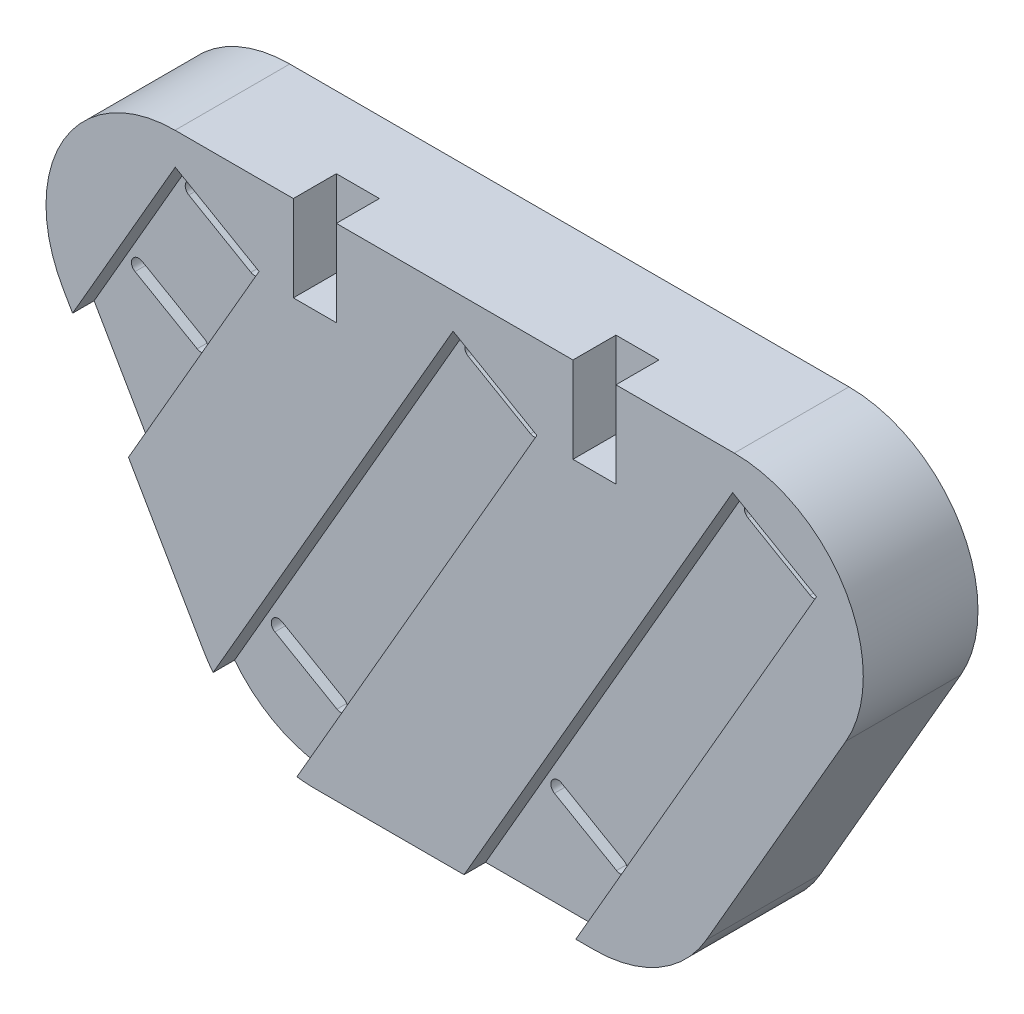
SolidWorks part; units mm, degrees
ref_plane "Front Plane" through (0, 0, 0) normal (0, 0, 1) x (1, 0, 0)
ref_plane "Top Plane" through (0, 0, 0) normal (0, 1, 0) x (1, 0, 0)
ref_plane "Right Plane" through (0, 0, 0) normal (1, 0, 0) x (0, 0, -1)
sketch "Sketch1" plane through (0, 0, 0) normal (0, 0, 1) x (1, 0, 0)
  line L0 (0, 0) -> (-19.5, 0) construction
  line L1 (-9.75, -16.8875) -> (-29.25, -16.8875) construction
  line L2 (0, 0) -> (-9.75, -16.8875) construction
  line L3 (-9.75, -16.8875) -> (-19.5, 0) construction
  line L4 (-19.5, 0) -> (-29.25, -16.8875) construction
  line L5 (-29.25, -16.8875) -> (-39, 0) construction
  line L6 (-39, 0) -> (-19.5, 0) construction
  line L7 (8.9827, 0.5584) -> (-5.4199, -24.3875) construction
  line L8 (-5.4199, -24.3875) -> (-33.5801, -24.3875) construction
  line L9 (-33.5801, -24.3875) -> (-47.9827, 0.5584) construction
  line L10 (-43.9749, 7.5) -> (4.9749, 7.5) construction
  line L11 (7.7942, -4.5) -> (-1.9558, -21.3875)
  line L12 (-9.75, -25.8875) -> (-29.25, -25.8875)
  line L13 (-37.0442, -21.3875) -> (-46.7942, -4.5)
  line L14 (-39, 9) -> (0, 9)
  line L15 (1.7814, -11.9145) -> (3.0804, -12.6645) construction
  line L16 (-19.5, -24.3875) -> (-19.5, -25.8875) construction
  line L17 (-40.7814, -11.9145) -> (-42.0804, -12.6645) construction
  line L18 (-19.5, 7.5) -> (-19.5, 9) construction
  circle A0 centre (-29.25, -16.8875) radius 7.5
  circle A1 centre (-19.5, 0) radius 7.5
  circle A2 centre (0, 0) radius 7.5
  circle A3 centre (0, 0) radius 7.5
  circle A4 centre (-9.75, -16.8875) radius 7.5
  circle A5 centre (-39, 0) radius 7.5
  arc A6 (7.7942, -4.5) -> (0, 9) centre (0, 0) ccw
  arc A7 (-39, 9) -> (-46.7942, -4.5) centre (-39, 0) ccw
  arc A8 (-1.9558, -21.3875) -> (-9.75, -25.8875) centre (-9.75, -16.8875) cw
  arc A9 (-29.25, -25.8875) -> (-37.0442, -21.3875) centre (-29.25, -16.8875) cw
  point P28 (1.7814, -11.9145)
  point P30 (-19.5, -24.3875)
  point P32 (-40.7814, -11.9145)
  point P35 (-19.5, 9)
  dimension "D2" = 15
  dimension "D3" = 19.5
  dimension "D4" = 1.5
  dimension "D5" = 1.5
  dimension "D1" = 0.25
extrude "Boss-Extrude1" add sketch "Sketch1" along normal blind 5
sketch "Sketch2" plane through (0, 0, 5) normal (0, 0, 1) x (1, 0, 0)
  line L0 (-1.9558, -21.3875) -> (7.7942, -4.5) construction
  line L1 (0, 9) -> (-39, 9) construction
  line L2 (-46.7942, -4.5) -> (-37.0442, -21.3875) construction
  line L3 (-29.25, -25.8875) -> (-9.75, -25.8875) construction
  line L4 (-1.9558, -21.3875) -> (7.7942, -4.5)
  line L5 (0, 9) -> (-39, 9)
  line L6 (-46.7942, -4.5) -> (-37.0442, -21.3875)
  line L7 (-29.25, -25.8875) -> (-9.75, -25.8875)
  line L8 (4.0401, 1.9976) -> (-0.2901, 4.4976) construction
  line L9 (3.7901, 1.5646) -> (-0.5401, 4.0646)
  line L10 (4.2901, 2.4306) -> (-0.0401, 4.9306)
  line L11 (-9.4599, -21.3851) -> (-13.7901, -18.8851) construction
  line L12 (-9.7099, -21.8181) -> (-14.0401, -19.3181)
  line L13 (-9.2099, -20.9521) -> (-13.5401, -18.4521)
  line L14 (1.875, 3.2476) -> (-11.625, -20.1351) construction
  line L15 (-31.125, -20.1351) -> (-29.25, -16.8875) construction
  line L16 (0, 0) -> (1.875, 3.2476) construction
  line L17 (1.875, 3.2476) -> (3.75, 6.4952) construction
  line L18 (-11.625, -20.1351) -> (-13.5, -23.3827) construction
  line L19 (-11.625, -20.1351) -> (-9.75, -16.8875) construction
  line L20 (-17.625, 3.2476) -> (-15.75, 6.4952) construction
  line L21 (-17.625, 3.2476) -> (-31.125, -20.1351) construction
  line L22 (-19.5, 0) -> (-17.625, 3.2476) construction
  line L23 (-31.125, -20.1351) -> (-33, -23.3827) construction
  line L24 (-15.4599, 1.9976) -> (-19.7901, 4.4976) construction
  line L25 (-15.7099, 1.5646) -> (-20.0401, 4.0646)
  line L26 (-15.2099, 2.4306) -> (-19.5401, 4.9306)
  line L27 (-28.9599, -21.3851) -> (-33.2901, -18.8851) construction
  line L28 (-29.2099, -21.8181) -> (-33.5401, -19.3181)
  line L29 (-28.7099, -20.9521) -> (-33.0401, -18.4521)
  line L30 (-34.9599, 1.9976) -> (-39.2901, 4.4976) construction
  line L31 (-35.2099, 1.5646) -> (-39.5401, 4.0646)
  line L32 (-34.7099, 2.4306) -> (-39.0401, 4.9306)
  line L33 (-38.7099, -4.4976) -> (-43.0401, -1.9976) construction
  line L34 (-38.9599, -4.9306) -> (-43.2901, -2.4306)
  line L35 (-38.4599, -4.0646) -> (-42.7901, -1.5646)
  line L36 (-37.125, 3.2476) -> (-40.875, -3.2476) construction
  line L37 (-37.125, 3.2476) -> (-35.25, 6.4952) construction
  line L38 (-40.875, -3.2476) -> (-42.75, -6.4952) construction
  line L39 (-37.125, 3.2476) -> (-39, 0) construction
  arc A0 (-9.75, -25.8875) -> (-1.9558, -21.3875) centre (-9.75, -16.8875) ccw construction
  arc A1 (7.7942, -4.5) -> (0, 9) centre (0, 0) ccw construction
  arc A2 (-39, 9) -> (-46.7942, -4.5) centre (-39, 0) ccw construction
  arc A3 (-37.0442, -21.3875) -> (-29.25, -25.8875) centre (-29.25, -16.8875) ccw construction
  arc A4 (-9.75, -25.8875) -> (-1.9558, -21.3875) centre (-9.75, -16.8875) ccw
  arc A5 (7.7942, -4.5) -> (0, 9) centre (0, 0) ccw
  arc A6 (-39, 9) -> (-46.7942, -4.5) centre (-39, 0) ccw
  arc A7 (-37.0442, -21.3875) -> (-29.25, -25.8875) centre (-29.25, -16.8875) ccw
  circle A8 centre (-39, 0) radius 7.5 construction
  circle A9 centre (-29.25, -16.8875) radius 7.5 construction
  circle A10 centre (-19.5, 0) radius 7.5 construction
  circle A11 centre (-9.75, -16.8875) radius 7.5 construction
  circle A12 centre (0, 0) radius 7.5 construction
  circle A13 centre (-39, 0) radius 7.5
  circle A14 centre (-29.25, -16.8875) radius 7.5
  circle A15 centre (-19.5, 0) radius 7.5
  circle A16 centre (-9.75, -16.8875) radius 7.5
  circle A17 centre (0, 0) radius 7.5
  arc A18 (3.7901, 1.5646) -> (4.2901, 2.4306) centre (4.0401, 1.9976) ccw
  arc A19 (-0.0401, 4.9306) -> (-0.5401, 4.0646) centre (-0.2901, 4.4976) ccw
  arc A20 (-9.7099, -21.8181) -> (-9.2099, -20.9521) centre (-9.4599, -21.3851) ccw
  arc A21 (-13.5401, -18.4521) -> (-14.0401, -19.3181) centre (-13.7901, -18.8851) ccw
  arc A22 (-15.7099, 1.5646) -> (-15.2099, 2.4306) centre (-15.4599, 1.9976) ccw
  arc A23 (-19.5401, 4.9306) -> (-20.0401, 4.0646) centre (-19.7901, 4.4976) ccw
  arc A24 (-29.2099, -21.8181) -> (-28.7099, -20.9521) centre (-28.9599, -21.3851) ccw
  arc A25 (-33.0401, -18.4521) -> (-33.5401, -19.3181) centre (-33.2901, -18.8851) ccw
  arc A26 (-35.2099, 1.5646) -> (-34.7099, 2.4306) centre (-34.9599, 1.9976) ccw
  arc A27 (-39.0401, 4.9306) -> (-39.5401, 4.0646) centre (-39.2901, 4.4976) ccw
  arc A28 (-38.9599, -4.9306) -> (-38.4599, -4.0646) centre (-38.7099, -4.4976) ccw
  arc A29 (-42.7901, -1.5646) -> (-43.2901, -2.4306) centre (-43.0401, -1.9976) ccw
  point P8 (-37.125, 3.2476)
  point P25 (1.875, 3.2476)
  point P32 (-11.625, -20.1351)
  point P45 (-17.625, 3.2476)
  point P52 (-31.125, -20.1351)
  point P64 (-40.875, -3.2476)
  circle M1 centre (-9.75, -16.8875) radius 7.5
  circle M2 centre (0, 0) radius 7.5
  arc M3 (7.7942, -4.5) -> (0, 9) centre (0, 0) ccw
  line M4 (0, 9) -> (-39, 9)
  arc M5 (-39, 9) -> (-46.7942, -4.5) centre (-39, 0) ccw
  line M6 (-46.7942, -4.5) -> (-37.0442, -21.3875)
  arc M7 (-37.0442, -21.3875) -> (-29.25, -25.8875) centre (-29.25, -16.8875) ccw
  line M8 (-29.25, -25.8875) -> (-9.75, -25.8875)
  arc M9 (-9.75, -25.8875) -> (-1.9558, -21.3875) centre (-9.75, -16.8875) ccw
  line M10 (-1.9558, -21.3875) -> (7.7942, -4.5)
  circle M11 centre (-19.5, 0) radius 7.5
  circle M12 centre (-29.25, -16.8875) radius 7.5
  circle M13 centre (-39, 0) radius 7.5
  dimension "D1" = 1
  dimension "D2" = 5
extrude "Boss-Extrude2" add sketch "Sketch2" along normal blind 1.5 contours A21 L13 A20 L12 M1 | M10 M3 M4 M5 M6 M7 M8 M9 M2 M11 M13 M12 M1 | A19 L10 A18 L9 M2 | A23 L26 A22 L25 M11 | A25 L29 A24 L28 M12 | A29 L35 A28 L34 A27 L32 A26 L31 M13
sketch "Sketch3" plane through (0, 0, 6.5) normal (0, 0, 1) x (1, 0, 0)
  line L0 (-46.7942, -4.5) -> (-37.0442, -21.3875) construction
  line L1 (-29.25, -25.8875) -> (-9.75, -25.8875) construction
  line L2 (-1.9558, -21.3875) -> (7.7942, -4.5) construction
  line L3 (0, 9) -> (-39, 9) construction
  line L4 (-46.7942, -4.5) -> (-37.0442, -21.3875)
  line L5 (-29.25, -25.8875) -> (-9.75, -25.8875)
  line L6 (-1.9558, -21.3875) -> (7.7942, -4.5)
  line L7 (0, 9) -> (-39, 9)
  line L8 (5.7353, 3.1839) -> (-9.6397, -23.4464)
  line L9 (5.7353, 3.1839) -> (-0.1103, 6.5589)
  line L10 (-9.6397, -23.4464) -> (-15.4853, -20.0714)
  line L11 (-0.1103, 6.5589) -> (-15.4853, -20.0714)
  line L12 (5.7353, 3.1839) -> (-15.4853, -20.0714) construction
  line L13 (-9.6397, -23.4464) -> (-0.1103, 6.5589) construction
  line L14 (-11.625, -20.1351) -> (-13.5, -23.3827) construction
  line L15 (-11.625, -20.1351) -> (-13.5, -23.3827) construction
  line L16 (-11.875, -20.5681) -> (-12.5625, -21.7589) construction
  line L17 (-9.7099, -21.8181) -> (-14.0401, -19.3181) construction
  line L18 (-14.2231, -18.6351) -> (-14.5478, -18.4476) construction
  line L19 (1.875, 3.2476) -> (-11.625, -20.1351) construction
  line L20 (1.875, 3.2476) -> (-11.625, -20.1351) construction
  line L21 (-31.125, -20.1351) -> (-33, -23.3827) construction
  line L22 (-17.625, 3.2476) -> (-31.125, -20.1351) construction
  line L23 (-31.125, -20.1351) -> (-33, -23.3827) construction
  line L24 (-17.625, 3.2476) -> (-31.125, -20.1351) construction
  line L25 (-13.7647, 3.1839) -> (-29.1397, -23.4464)
  line L26 (-13.7647, 3.1839) -> (-19.6103, 6.5589)
  line L27 (-29.1397, -23.4464) -> (-34.9853, -20.0714)
  line L28 (-19.6103, 6.5589) -> (-34.9853, -20.0714)
  line L29 (-13.7647, 3.1839) -> (-34.9853, -20.0714) construction
  line L30 (-29.1397, -23.4464) -> (-19.6103, 6.5589) construction
  line L31 (-32.8571, -19.1351) -> (-34.0478, -18.4476) construction
  line L32 (-31.375, -20.5681) -> (-32.0625, -21.7589) construction
  line L33 (-29.2099, -21.8181) -> (-33.5401, -19.3181) construction
  line L34 (-33.1397, 3.4004) -> (-42.2476, -12.375)
  line L35 (-33.1397, 3.4004) -> (-38.9853, 6.7754)
  line L36 (-9.6397, -23.4464) -> (-15.4853, -20.0714)
  line L37 (-38.9853, 6.7754) -> (-46.1447, -5.625)
  line L38 (-33.1397, 3.4004) -> (-45.4579, -6.8146) construction
  line L39 (-42.2476, -12.375) -> (-38.9853, 6.7754) construction
  line L40 (-37.125, 3.2476) -> (-40.875, -3.2476) construction
  line L41 (-36.875, 3.6806) -> (-36.0625, 5.0879) construction
  line L42 (-34.7099, 2.4306) -> (-39.0401, 4.9306) construction
  line L43 (-36.0625, 5.0879) -> (-35.25, 6.4952) construction
  line L44 (-9.6397, -23.4464) -> (-11.049, -25.8875)
  line L45 (-15.4853, -20.0714) -> (-18.8433, -25.8875)
  line L47 (-29.1397, -23.4464) -> (-34.9853, -20.0714)
  line L48 (-29.1397, -23.4464) -> (-30.4988, -25.8004)
  line L49 (-34.9853, -20.0714) -> (-36.3444, -22.4254)
  arc A0 (-37.0442, -21.3875) -> (-29.25, -25.8875) centre (-29.25, -16.8875) ccw construction
  arc A1 (-9.75, -25.8875) -> (-1.9558, -21.3875) centre (-9.75, -16.8875) ccw construction
  arc A2 (7.7942, -4.5) -> (0, 9) centre (0, 0) ccw construction
  arc A3 (-39, 9) -> (-46.7942, -4.5) centre (-39, 0) ccw construction
  arc A4 (-37.0442, -21.3875) -> (-29.25, -25.8875) centre (-29.25, -16.8875) ccw
  arc A5 (-9.75, -25.8875) -> (-1.9558, -21.3875) centre (-9.75, -16.8875) ccw
  arc A6 (7.7942, -4.5) -> (0, 9) centre (0, 0) ccw
  arc A7 (-39, 9) -> (-46.7942, -4.5) centre (-39, 0) ccw
  arc A8 (-13.5401, -18.4521) -> (-14.0401, -19.3181) centre (-13.7901, -18.8851) ccw construction
  arc A9 (-33.0401, -18.4521) -> (-33.5401, -19.3181) centre (-33.2901, -18.8851) ccw construction
  point P13 (-4.875, -8.4437)
  point P30 (-12.5625, -21.7589)
  point P33 (-4.875, -8.4437)
  point P35 (-24.375, -8.4437)
  point P49 (-24.375, -8.4437)
  point P50 (-40.6165, -2.7998)
  line M15 (-1.9558, -21.3875) -> (7.7942, -4.5)
  arc M16 (7.7942, -4.5) -> (0, 9) centre (0, 0) ccw
  line M17 (0, 9) -> (-39, 9)
  arc M18 (-39, 9) -> (-46.7942, -4.5) centre (-39, 0) ccw
  line M19 (-46.7942, -4.5) -> (-37.0442, -21.3875)
  arc M20 (-37.0442, -21.3875) -> (-29.25, -25.8875) centre (-29.25, -16.8875) ccw
  line M21 (-29.25, -25.8875) -> (-9.75, -25.8875)
  arc M22 (-9.75, -25.8875) -> (-1.9558, -21.3875) centre (-9.75, -16.8875) ccw
extrude "Boss-Extrude3" add sketch "Sketch3" along normal blind 1.5 contours L37 L35 L34 L4 L28 L26 L25 L27 L11 L9 L8 L10 M20 M21 M22 M15 M16 M17 M18 M19
sketch "Sketch9" plane through (0, 0, 8) normal (0, 0, 1) x (1, 0, 0)
  line L0 (-39, 9) -> (-19.5, 9)
  line L1 (0, 9) -> (-39, 9) construction
  line L2 (-19.5, 9) -> (0, 9) construction
  line L3 (-29.25, 9) -> (-29.25, 3) construction
  line L4 (-27.75, 3) -> (-30.75, 3)
  line L5 (-27.75, 3) -> (-27.75, 9)
  line L6 (-27.75, 9) -> (-30.75, 9)
  line L7 (-30.75, 3) -> (-30.75, 9)
  line L8 (-27.75, 3) -> (-30.75, 9) construction
  line L9 (-27.75, 9) -> (-30.75, 3) construction
  line L10 (-8.25, 3) -> (-11.25, 3)
  line L11 (-8.25, 3) -> (-8.25, 9)
  line L12 (-8.25, 9) -> (-11.25, 9)
  line L13 (-11.25, 3) -> (-11.25, 9)
  line L14 (-8.25, 3) -> (-11.25, 9) construction
  line L15 (-8.25, 9) -> (-11.25, 3) construction
  line L16 (-9.75, 9) -> (-9.75, 3) construction
  point P5 (-29.25, 6)
  point P12 (-9.75, 6)
  dimension "D1" = 3
  dimension "D2" = 6
extrude "Cut-Extrude4" cut sketch "Sketch9" against normal blind 3 contours L10 L13 L12 L11 | L4 L7 L6 L5
sketch "Sketch4" plane through (0, 0, 0) normal (0, 0, -1) x (-1, 0, 0)
  line L0 (29.25, -25.8875) -> (9.75, -25.8875) construction
  line L1 (22, -25.8875) -> (17, -25.8875)
  line L2 (22, -25.8875) -> (22, -22.8875)
  line L3 (22, -22.8875) -> (17, -22.8875)
  line L4 (17, -25.8875) -> (17, -22.8875)
  line L5 (22, -25.8875) -> (17, -22.8875) construction
  line L6 (22, -22.8875) -> (17, -25.8875) construction
  line L7 (29.25, -25.8875) -> (9.75, -25.8875)
  line L8 (0, 9) -> (39, 9) construction
  line L9 (46.7942, -4.5) -> (37.0442, -21.3875) construction
  line L10 (1.9558, -21.3875) -> (-7.7942, -4.5) construction
  line L11 (0, 9) -> (39, 9)
  line L12 (46.7942, -4.5) -> (37.0442, -21.3875)
  line L13 (1.9558, -21.3875) -> (-7.7942, -4.5)
  line L14 (40.5712, -9.2787) -> (43.1692, -10.7787)
  line L15 (40.5712, -9.2787) -> (38.0712, -13.6088)
  line L16 (43.1692, -10.7787) -> (40.6692, -15.1088)
  line L17 (38.0712, -13.6088) -> (40.6692, -15.1088)
  line L18 (40.5712, -9.2787) -> (40.6692, -15.1088) construction
  line L19 (43.1692, -10.7787) -> (38.0712, -13.6088) construction
  line L20 (-1.5712, -9.2787) -> (-4.1692, -10.7787)
  line L21 (-1.5712, -9.2787) -> (0.9288, -13.6088)
  line L22 (-4.1692, -10.7787) -> (-1.6692, -15.1088)
  line L23 (0.9288, -13.6088) -> (-1.6692, -15.1088)
  line L24 (-1.5712, -9.2787) -> (-1.6692, -15.1088) construction
  line L25 (-4.1692, -10.7787) -> (0.9288, -13.6088) construction
  line L26 (41.9192, -12.9437) -> (3.9115, 9) construction
  line L27 (12.25, 6) -> (7.25, 6)
  line L28 (12.25, 6) -> (12.25, 9)
  line L29 (12.25, 9) -> (7.25, 9)
  line L30 (7.25, 6) -> (7.25, 9)
  line L31 (12.25, 6) -> (7.25, 9) construction
  line L32 (12.25, 9) -> (7.25, 6) construction
  line L33 (31.75, 6) -> (26.75, 6)
  line L34 (31.75, 6) -> (31.75, 9)
  line L35 (31.75, 9) -> (26.75, 9)
  line L36 (26.75, 6) -> (26.75, 9)
  line L37 (31.75, 6) -> (26.75, 9) construction
  line L38 (31.75, 9) -> (26.75, 6) construction
  line L39 (-2.9192, -12.9437) -> (35.0885, 9) construction
  line L40 (22, -24.3875) -> (17, -24.3875)
  line L41 (-0.3702, -14.3588) -> (-2.8702, -10.0287)
  line L42 (12.25, 7.5) -> (7.25, 7.5)
  line L43 (39.3702, -14.3588) -> (41.8702, -10.0287)
  line L44 (26.75, 7.5) -> (31.75, 7.5)
  point P0 (19.5, -24.3875)
  point P5 (9.75, 7.5)
  point P8 (19.5, -25.8875)
  point P15 (40.6202, -12.1937)
  point P16 (-1.6202, -12.1937)
  point P29 (29.25, 7.5)
  dimension "D1" = 5
  dimension "D2" = 3
extrude "Cut-Extrude5" cut sketch "Sketch4" against normal blind 3 contours L41 L23 L21 L20 | L28 L42 L30 L27 | L44 L36 L33 L34 | L17 L43 L14 L15 | L40 L2 L3 L4
equation "\"D3@Sketch1\"=\"D2@Sketch1\"+4.5"
equation "\"D1@Sketch2\"=.65+.35"
